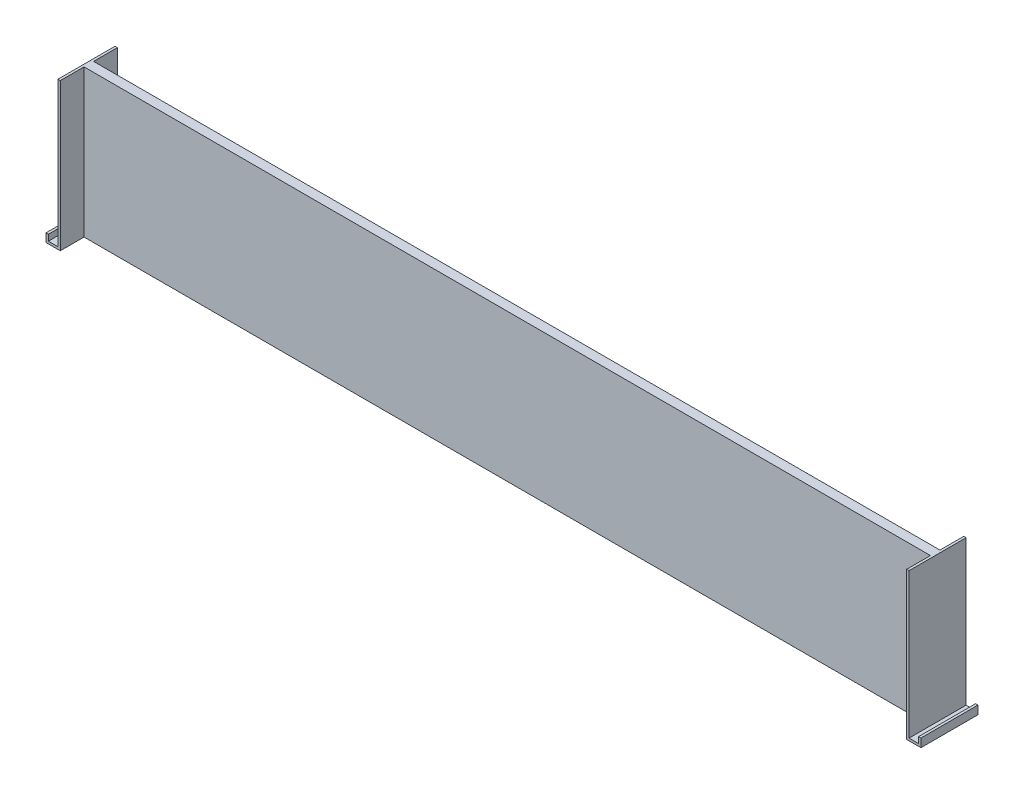
SolidWorks part; units mm, degrees
ref_plane "Front Plane" through (0, 0, 0) normal (0, 0, 1) x (1, 0, 0)
ref_plane "Top Plane" through (0, 0, 0) normal (0, 1, 0) x (1, 0, 0)
ref_plane "Right Plane" through (0, 0, 0) normal (1, 0, 0) x (0, 0, -1)
sketch "Sketch1" plane through (0, 0, 0) normal (0, 1, 0) x (1, 0, 0)
  line L1 (0, 0) -> (282.575, 0)
  line L2 (0, 0) -> (0, 3.175)
  line L3 (0, 3.175) -> (282.575, 3.175)
  line L4 (282.575, 0) -> (282.575, 3.175)
  line L5 (0, -7.9375) -> (-4.7625, -7.9375)
  line L6 (0, -7.9375) -> (0, 11.1125)
  line L7 (0, 11.1125) -> (-4.7625, 11.1125)
  line L8 (-4.7625, -7.9375) -> (-4.7625, 11.1125)
  line L9 (282.575, -7.9375) -> (287.3375, -7.9375)
  line L10 (282.575, -7.9375) -> (282.575, 11.1125)
  line L11 (282.575, 11.1125) -> (287.3375, 11.1125)
  line L12 (287.3375, -7.9375) -> (287.3375, 11.1125)
  point P5 (0, 1.5875)
  point P14 (0, 1.5875)
  point P15 (282.575, 1.5875)
  point P16 (282.575, 1.5875)
  dimension "D1" = 282.575
  dimension "D2" = 3.175
  dimension "D3" = 4.7625
  dimension "D4" = 4.7625
  dimension "D5" = 19.05
  dimension "D6" = 19.05
extrude "Boss-Extrude1" add sketch "Sketch1" along normal blind 49.2125 contours L8 L5 L6 L2 L7 | L9 L12 L11 L10 L4
sketch "Sketch2" plane through (0, 0, 7.9375) normal (0, 0, 1) x (1, 0, 0)
  line L0 (-4.7625, 2.8185) -> (-3.9688, 2.8185)
  line L1 (-4.7625, 49.2125) -> (-4.7625, 0) construction
  line L2 (-3.9688, 2.8185) -> (-3.9688, 0.7937)
  line L3 (-3.9688, 0.7937) -> (-0.7938, 0.7937)
  line L4 (-0.7938, 0.7937) -> (-0.7938, 49.2125)
  line L5 (0, 49.2125) -> (-4.7625, 49.2125) construction
  line L6 (-0.7938, 49.2125) -> (-4.7625, 49.2125)
  line L7 (-4.7625, 49.2125) -> (-4.7625, 2.8185)
  line L8 (0, 0) -> (-4.7625, 0) construction
  line L9 (287.3375, 2.8185) -> (286.5437, 2.8185)
  line L10 (286.5437, 2.8185) -> (286.5437, 0.7938)
  line L11 (286.5437, 0.7938) -> (283.3687, 0.7938)
  line L12 (283.3687, 0.7938) -> (283.3687, 49.2125)
  line L13 (283.3687, 49.2125) -> (287.3375, 49.2125)
  line L14 (287.3375, 49.2125) -> (287.3375, 2.8185)
  line L15 (282.575, 49.2125) -> (287.3375, 49.2125) construction
  line L16 (287.3375, 49.2125) -> (287.3375, 0) construction
  line L17 (282.575, 0) -> (287.3375, 0) construction
  point P13 (-2.3813, 0)
  point P14 (-2.3813, 0.7937)
  point P21 (284.9562, 0.7938)
  point P28 (284.9562, 0)
  dimension "D1" = 3.175
  dimension "D2" = 0.7937
  dimension "D3" = 3.175
  dimension "D4" = 0.7938
extrude "Cut-Extrude1" cut sketch "Sketch2" against normal through all
